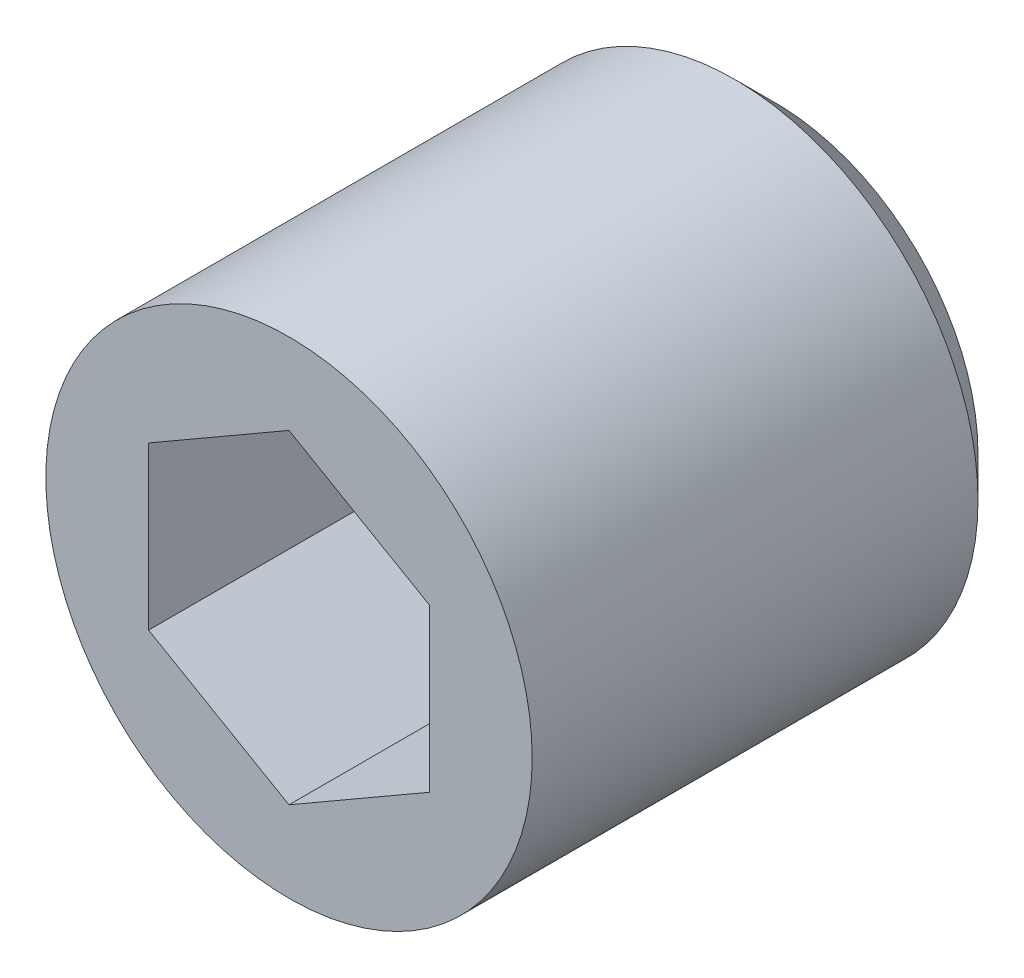
SolidWorks part; units mm, degrees
material "Alliage de zinc AC41A, brut"
ref_plane "Plan de face" through (0, 0, 0) normal (0, 0, 1) x (1, 0, 0)
ref_plane "Plan de dessus" through (0, 0, 0) normal (0, 1, 0) x (1, 0, 0)
ref_plane "Plan de droite" through (0, 0, 0) normal (1, 0, 0) x (0, 0, -1)
sketch "Esquisse1" plane through (0, 0, 0) normal (0, 0, 1) x (1, 0, 0)
  circle A0 centre (0, 0) radius 3
  dimension "D1" = 6
extrude "Boss.-Extru.1" add sketch "Esquisse1" along normal blind 6
cosmetic thread "Représentation de filetage1" parameters "D2"=5
chamfer "Chanfrein1" distance 0.5 angle 45 1 edges at (3, 0, 0)
sketch "Esquisse9" plane through (0, 0, 6) normal (0, 0, 1) x (1, 0, 0)
  point P0 (0, 0)
hole_wizard "Diamètre du perçage Ø4.0 (4)1" positions "Esquisse9" profile "Esquisse8" hole size "Ø4.0" standard "ISO"
sketch "Esquisse8" plane through (0, 0, 6) normal (1, 0, 0) x (0, -1, 0)
  line L0 (0, 0) -> (0, 5)
  line L1 (0, 5) -> (2, 3.7983)
  line L2 (2, 3.7983) -> (2, 0)
  line L5 (2, 0) -> (0, 0)
  line L10 (0, 5) -> (-2, 3.7983) construction
  line L11 (0, -6.35) -> (0, 107.95) construction
  dimension "Diamètre du perçage" = 4
  dimension "Profondeur du perçage" = 5
  dimension "Angle de pointe" = 118
sketch "Esquisse2" plane through (0, 0, 6) normal (0, 0, 1) x (1, 0, 0)
  line L0 (0, 2) -> (1.7321, 1)
  line L5 (1.7321, 1) -> (1.7321, -1)
  line L6 (1.7321, -1) -> (0, -2)
  line L7 (0, -2) -> (-1.7321, -1)
  line L8 (-1.7321, -1) -> (-1.7321, 1)
  line L9 (-1.7321, 1) -> (0, 2)
  circle A0 centre (0, 0) radius 2 construction
  circle A1 centre (0, 0) radius 3
  point P17 (0, 0)
  dimension "D1" = 6
  dimension "D2" = 2
  dimension "D3" = 4
  dimension "D4" = 3
extrude "Boss.-Extru.3" add sketch "Esquisse2" against normal blind 5
sketch "Esquisse5" plane through (0, 0, 0) normal (0, 0, -1) x (-1, 0, 0)
  point P0 (0, 0)
hole_wizard "Diamètre du perçage Ø1.0 (1)1" positions "Esquisse5" profile "Esquisse4" hole size "Ø1.0" standard "ISO"
sketch "Esquisse4" plane through (0, 0, 0) normal (1, 0, 0) x (0, 1, 0)
  line L0 (0, 0) -> (0, 1.8004)
  line L1 (0, 1.8004) -> (0.5, 1.5)
  line L2 (0.5, 1.5) -> (0.5, 0)
  line L5 (0.5, 0) -> (0, 0)
  line L10 (0, 1.8004) -> (-0.5, 1.5) construction
  line L11 (0, -6.35) -> (0, 107.95) construction
  dimension "Diamètre du perçage" = 1
  dimension "Profondeur du perçage" = 1.5
  dimension "Angle de pointe" = 118
